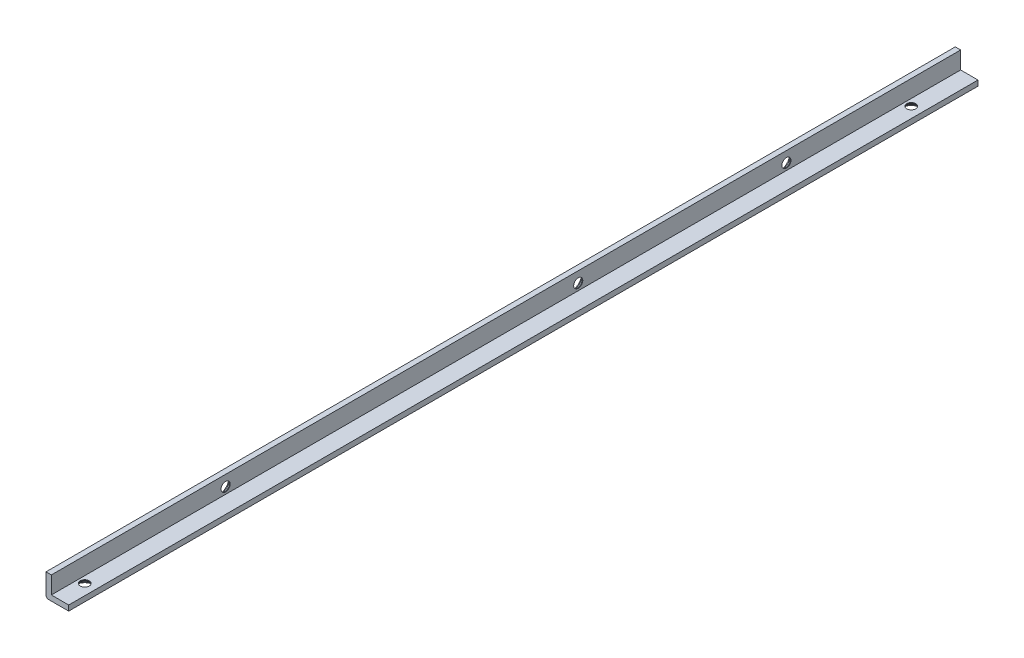
SolidWorks part; units mm, degrees
material "7075-T6 (SN)"
ref_plane "Front Plane" through (0, 0, 0) normal (0, 0, 1) x (1, 0, 0)
ref_plane "Top Plane" through (0, 0, 0) normal (0, 1, 0) x (1, 0, 0)
ref_plane "Right Plane" through (0, 0, 0) normal (1, 0, 0) x (0, 0, -1)
sketch "Sketch1" plane through (0, 0, 0) normal (0, 0, 1) x (1, 0, 0)
  line L0 (0, 0) -> (-8.5, 0)
  line L1 (-8.5, 0) -> (-8.5, 8.5)
  line L2 (-8.5, 8.5) -> (-6.5, 8.5)
  line L3 (-6.5, 8.5) -> (-6.5, 2)
  line L4 (-6.5, 2) -> (0, 2)
  line L5 (0, 2) -> (0, 0)
  dimension "D1" = 2
  dimension "D2" = 2
  dimension "D3" = 8.5
  dimension "D4" = 8.5
extrude "Boss-Extrude1" add sketch "Sketch1" along normal blind 340.5
fillet "Fillet1" radius 1 1 edges at (-8.5, 0, 170.25)
ref_plane "Plane1" through (0, 0, 170.25) normal (0, 0, 1) x (1, 0, 0)
sketch "Sketch2" plane through (0, 2, 0) normal (0, 1, 0) x (1, 0, 0)
  point P0 (-4, -330.5)
  point P1 (-4, -21)
  point P6 (-4, -21)
sketch "Sketch3" plane through (-6.5, 0, 0) normal (1, 0, 0) x (0, 0, -1)
  point P0 (-275.25, 4.5)
  point P1 (-143.2, 4.5)
  point P2 (-65.25, 4.5)
sketch "Sketch4" plane through (0, 0, 0) normal (0, -1, 0) x (1, 0, 0)
  point P0 (-4, 21)
  point P2 (-4, 330.5)
  point P4 (-6.5, 65.25)
  point P6 (-6.5, 143.2)
  point P8 (-6.5, 275.25)
sketch "Sketch6" plane through (-8.5, 0, 0) normal (-1, 0, 0) x (0, 0, 1)
  point P0 (65.25, 4.5)
  point P2 (143.2, 4.5)
  point P4 (275.25, 4.5)
hole_wizard "CSK for M3 Countersunk Flat Head Screw1" positions "3DSketch2" profile "Sketch7" countersink size "M3" standard "ISO"
sketch3d "3DSketch2"
  point P0 (-4, 0, 330.5)
  point P3 (-8.5, 4.5, 275.25)
  point P6 (-8.5, 4.5, 143.2)
  point P9 (-8.5, 4.5, 65.25)
  point P12 (-4, 0, 21)
sketch "Sketch7" plane through (-4, 0, 330.5) normal (1, 0, 0) x (0, 0, -1)
  line L0 (0, 0) -> (0, 10.5215)
  line L1 (0, 10.5215) -> (1.7, 9.5)
  line L2 (1.7, 9.5) -> (1.7, 1.75)
  line L3 (1.7, 1.75) -> (3.15, 0.3)
  line L4 (3.15, 0.3) -> (3.15, 0)
  line L6 (3.15, 0) -> (0, 0)
  line L7 (-1.7, 1.75) -> (-3.15, 0.3) construction
  line L10 (0, 10.5215) -> (-1.7, 9.5) construction
  line L11 (0, -6.35) -> (0, 107.95) construction
  dimension "Hole Dia." = 3.4
  dimension "Hole Depth" = 9.5
  dimension "C'Sink Dia." = 6.3
  dimension "C'Sink Angle" = 90
  dimension "Drill Angle" = 118
  dimension "Head Clearance" = 0.3
equation "\"thickness\"= 2mm"
equation "\"D1@Sketch1\"=\"thickness\""
equation "\"D2@Sketch1\"=\"D1@Sketch1\""
equation "\"D4@Sketch1\"=\"D3@Sketch1\""
